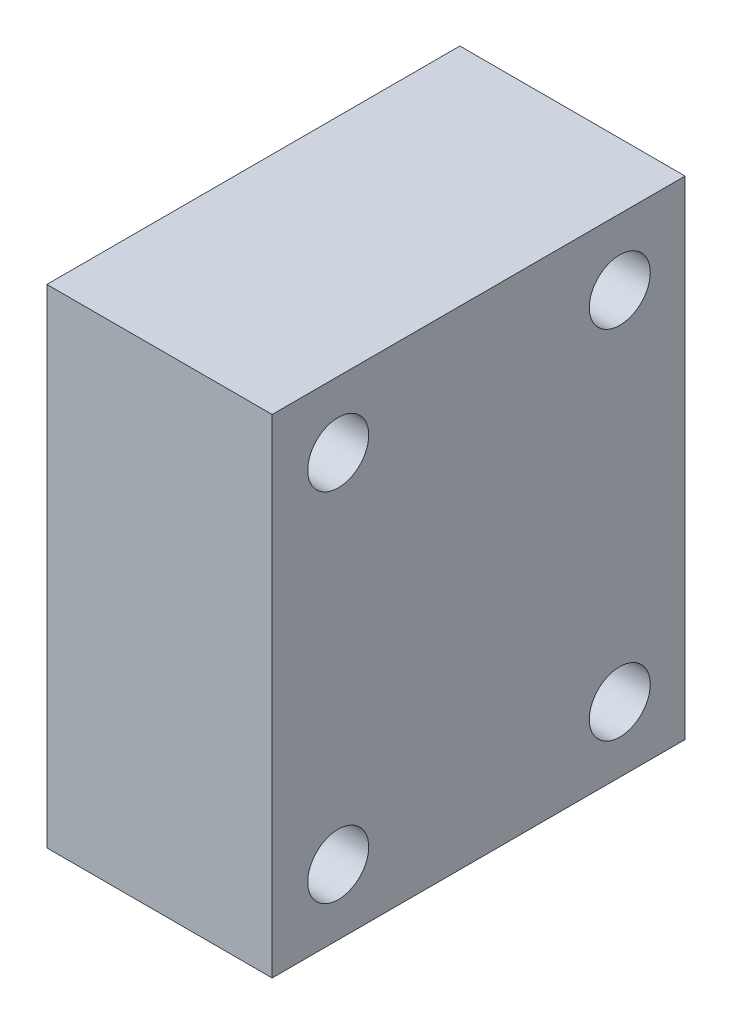
SolidWorks part; units mm, degrees
ref_plane "Front Plane" through (0, 0, 0) normal (1, 0, 0) x (0, 1, 0)
ref_plane "Top Plane" through (0, 0, 0) normal (0, 0, 1) x (0, 1, 0)
ref_plane "Right Plane" through (0, 0, 0) normal (0, 1, 0) x (-1, 0, 0)
sketch "Sketch1" plane through (0, 0, 0) normal (1, 0, 0) x (0, 1, 0)
  line L1 (0, 0) -> (82.55, 0)
  line L2 (0, 0) -> (0, 69.85)
  line L3 (0, 69.85) -> (82.55, 69.85)
  line L4 (82.55, 0) -> (82.55, 69.85)
extrude "Boss-Extrude1" add sketch "Sketch1" along normal blind 38.1
sketch "Sketch2" plane through (0, 0, 0) normal (1, 0, 0) x (0, 1, 0)
  circle A0 centre (11.049, 11.049) radius 5.1594
  circle A1 centre (71.374, 11.049) radius 5.1594
  circle A2 centre (11.049, 58.674) radius 5.1594
  circle A3 centre (71.374, 58.674) radius 5.1594
extrude "Cut-Extrude2" cut sketch "Sketch2" along normal through all
sketch "Sketch3" plane through (0, 0, 0) normal (1, 0, 0) x (0, 1, 0)
  circle A0 centre (23.622, 34.798) radius 7.3422
  circle A1 centre (58.674, 34.798) radius 7.3422
extrude "Cut-Extrude3" cut sketch "Sketch3" along normal blind 28.448
sketch "Sketch4" plane through (0, 0, 0) normal (1, 0, 0) x (0, 1, 0)
  circle A0 centre (23.622, 34.798) radius 12.7254
  circle A1 centre (58.674, 34.798) radius 12.7254
extrude "Cut-Extrude4" cut sketch "Sketch4" along normal blind 2.8194
sketch "Sketch5" plane through (0, 0, 0) normal (0, 1, 0) x (-1, 0, 0)
  circle A0 centre (19.05, 34.798) radius 7.3422
sketch "Sketch6" plane through (0, 0, 0) normal (1, 0, 0) x (0, 1, 0)
  line L0 (0, 27.4558) -> (0, 42.1402) construction
  circle A0 centre (0, 41.275) radius 12.7254
extrude "Cut-Extrude7" cut sketch "Sketch6" along normal blind 2.8194
